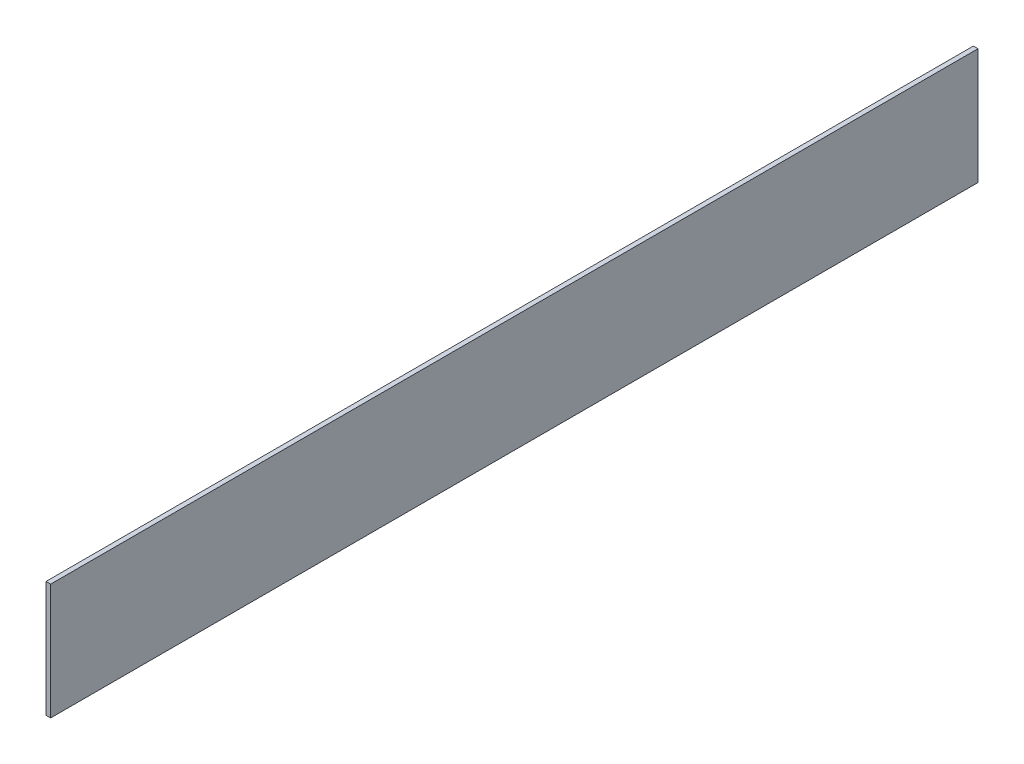
SolidWorks part; units mm, degrees
ref_plane "Front Plane" through (0, 0, 0) normal (0, 0, 1) x (1, 0, 0)
ref_plane "Top Plane" through (0, 0, 0) normal (0, 1, 0) x (1, 0, 0)
ref_plane "Right Plane" through (0, 0, 0) normal (1, 0, 0) x (0, 0, -1)
other "Configuration Table"
sketch "Sketch1" plane through (0, 0, 0) normal (0, 0, 1) x (1, 0, 0)
  line L1 (0, 1.6) -> (1.6, 1.6)
  line L2 (0, 1.6) -> (0, 41.6)
  line L3 (0, 41.6) -> (1.6, 41.6)
  line L4 (1.6, 1.6) -> (1.6, 41.6)
extrude "KUTU_duvar_sol_1" add sketch "Sketch1" against normal blind 320 separate body
